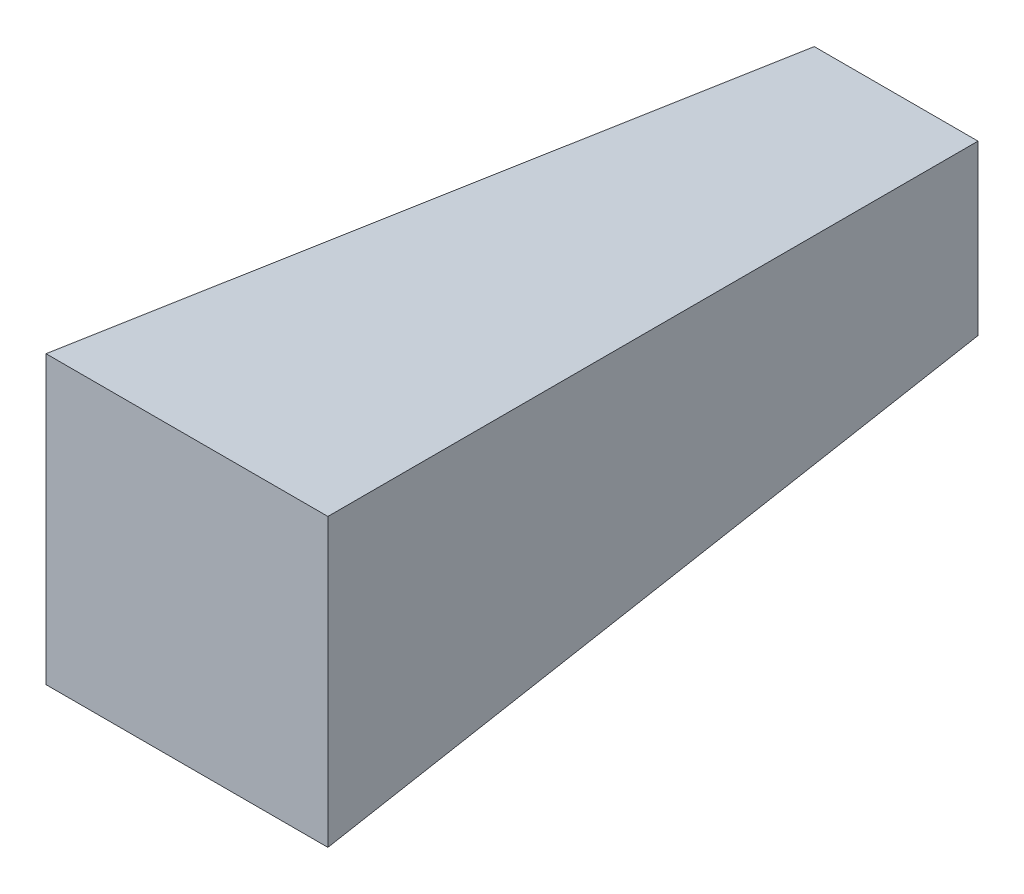
SolidWorks part; units mm, degrees
ref_plane "Front Plane" through (0, 0, 0) normal (0, 0, 1) x (1, 0, 0)
ref_plane "Top Plane" through (0, 0, 0) normal (0, 1, 0) x (1, 0, 0)
ref_plane "Right Plane" through (0, 0, 0) normal (1, 0, 0) x (0, 0, -1)
sketch "Sketch1" plane through (0, 0, 0) normal (0, 0, 1) x (1, 0, 0)
  line L1 (0, 0) -> (138.49, 0)
  line L2 (0, 0) -> (0, 142.4779)
  line L3 (0, 142.4779) -> (138.49, 142.4779)
  line L4 (138.49, 0) -> (138.49, 142.4779)
  dimension "D1" = 138.49
ref_plane "Plane1" through (0, 0, 600) normal (0, 0, 1) x (1, 0, 0)
sketch "Sketch2" plane through (0, 0, 600) normal (0, 0, 1) x (1, 0, 0)
  line L8 (-50, 192.4779) -> (-50, -50)
  line L9 (-50, -50) -> (188.49, -50)
  line L10 (188.49, -50) -> (188.49, 192.4779)
  line L11 (188.49, 192.4779) -> (-50, 192.4779)
  line L12 (-50, 192.4779) -> (-50, -50)
  line L13 (-50, -50) -> (188.49, -50)
  line L14 (188.49, -50) -> (188.49, 192.4779)
  line L15 (188.49, 192.4779) -> (-50, 192.4779)
  dimension "D1" = 50
loft "Loft1" add profiles "Sketch2", "Sketch1"
